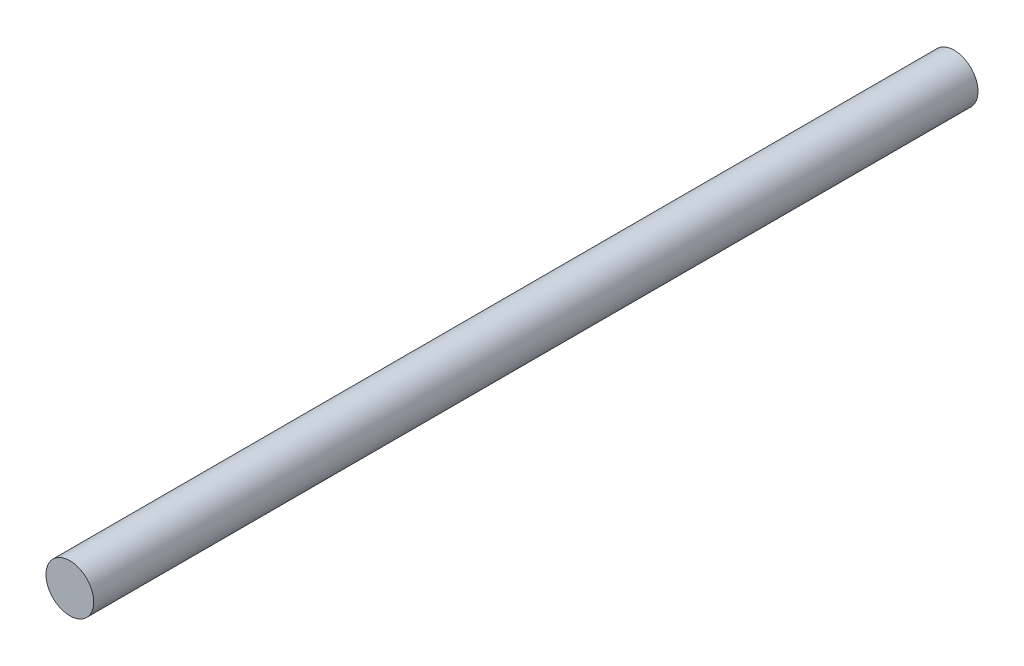
SolidWorks part; units mm, degrees
material "PP Copolymer"
ref_plane "Frontal" through (0, 0, 0) normal (0, 0, 1) x (1, 0, 0)
ref_plane "Superior " through (0, 0, 0) normal (0, 1, 0) x (1, 0, 0)
ref_plane "Lateral" through (0, 0, 0) normal (1, 0, 0) x (0, 0, -1)
sketch "Sketch1" plane through (0, 0, 0) normal (0, 0, 1) x (1, 0, 0)
  circle A0 centre (0, 0) radius 2.7
  dimension "D1" = 5.4
extrude "Base-Extrude" add sketch "Sketch1" against normal blind 100
sketch "Esboço1" plane through (0, 0, 0) normal (1, 0, 0) x (0, 0, -1)
  circle A0 centre (0, 0) radius 6.8941
extrude "Corte-extrusão1" [suppressed] cut sketch "Esboço1" along normal blind 6
other "Cavidade1" [suppressed]
other "Corpo NP com trava (PADRÃO - Molde Lambecht - Compactor)<1>@Neo-Pen Gigante1"
other "Ponta Neo-Pen<1>@Neo-Pen Gigante1"
sketch "Esboço2" [suppressed] plane through (0, 0, 0) normal (1, 0, 0) x (0, 0, -1)
  line L0 (0, 0) -> (4.8546, 0) construction
  line L1 (0, 0) -> (0, 0.95)
  line L3 (1.388, 0.95) -> (0, 0.95)
  line L4 (0, 2.7) -> (0, -2.7) construction
  line L5 (0, 0) -> (4.3118, 0)
  line L7 (4.3118, 0) -> (1.388, 0.95)
revolve "Corte-Revolução2" [suppressed] cut sketch "Esboço2" angle 360 about L0
sketch "Esboço3" [suppressed] plane through (0, 0, 0) normal (0, 1, 0) x (1, 0, 0)
  line L0 (-0.5201, 2.7112) -> (-1.393, 0.0245) construction
  line L1 (0, 4.3118) -> (-1.393, 0.0245)
  line L2 (0, 0) -> (0, 5.0395) construction
  line L3 (0, 0) -> (-1.393, 0)
  line L4 (-1.393, 0.0245) -> (-1.393, 0) construction
  line L5 (-1.393, 0.0245) -> (-1.393, 0)
  line L6 (0, 0) -> (0, 4.3118)
revolve "Corte-Revolução3" [suppressed] cut sketch "Esboço3" angle 360 about L2
sketch "Esboço4" plane through (0, 0, -100) normal (0, 0, 1) x (1, 0, 0)
  circle A0 centre (0, 0) radius 1.4
  dimension "D1" = 2.8
extrude "Corte-extrusão2" cut sketch "Esboço4" along normal blind 6.5
